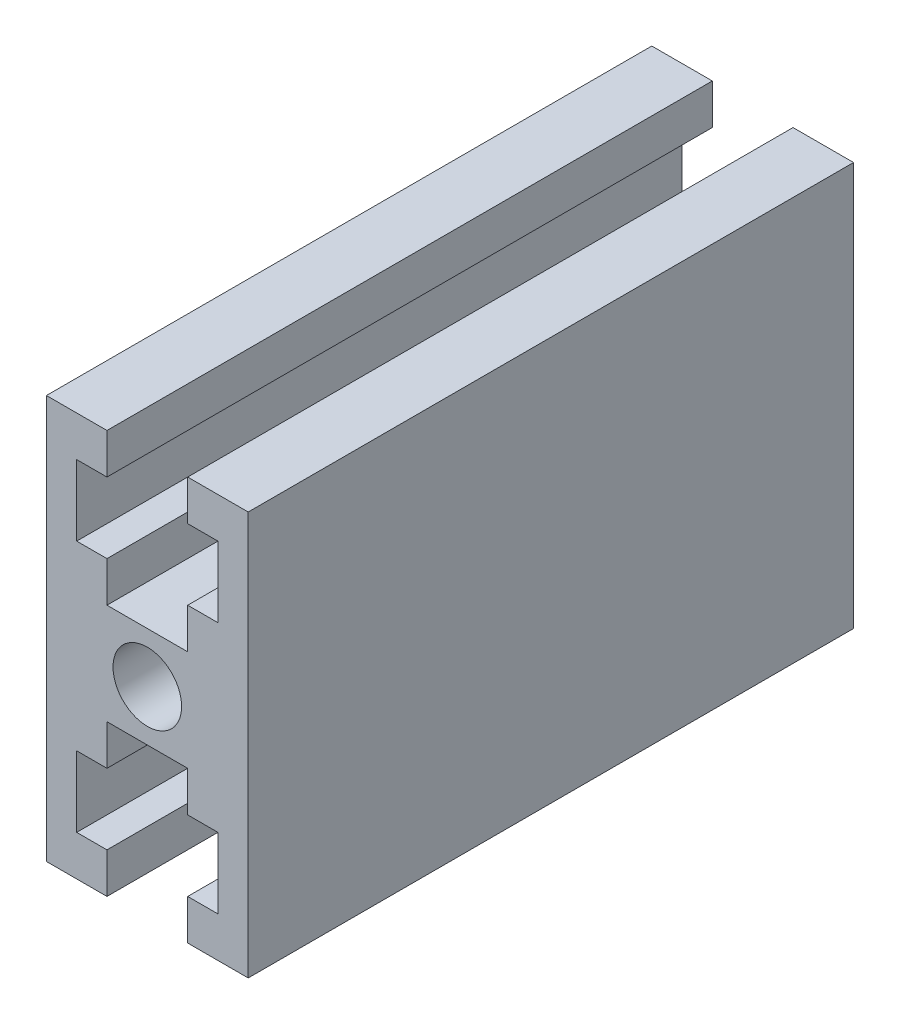
SolidWorks part; units mm, degrees
ref_plane "前视" through (0, 0, 0) normal (0, 0, 1) x (1, 0, 0)
ref_plane "上视" through (0, 0, 0) normal (0, 1, 0) x (1, 0, 0)
ref_plane "右视" through (0, 0, 0) normal (1, 0, 0) x (0, 0, -1)
sketch "草图2" plane through (0, 0, 0) normal (0, 0, 1) x (1, 0, 0)
  line L0 (0, 0) -> (6, 0)
  line L1 (6, 0) -> (6, -4)
  line L2 (6, -4) -> (3, -4)
  line L3 (3, -4) -> (3, -11)
  line L4 (3, -11) -> (6, -11)
  line L5 (6, -11) -> (6, -15)
  line L6 (6, -15) -> (14, -15)
  line L7 (14, -15) -> (14, -11)
  line L8 (14, -11) -> (17, -11)
  line L9 (17, -11) -> (17, -4)
  line L10 (17, -4) -> (14, -4)
  line L11 (14, -4) -> (14, 0)
  line L12 (14, 0) -> (20, 0)
  line L13 (20, 0) -> (20, -40)
  line L14 (0, 0) -> (0, -40)
  line L15 (-88.7936, -20) -> (42.7765, -20) construction
  line L16 (14, -40) -> (20, -40)
  line L17 (14, -36) -> (14, -40)
  line L18 (17, -36) -> (14, -36)
  line L19 (17, -29) -> (17, -36)
  line L20 (14, -29) -> (17, -29)
  line L21 (14, -25) -> (14, -29)
  line L22 (6, -25) -> (14, -25)
  line L23 (6, -29) -> (6, -25)
  line L24 (3, -29) -> (6, -29)
  line L25 (3, -36) -> (3, -29)
  line L26 (6, -36) -> (3, -36)
  line L27 (6, -40) -> (6, -36)
  line L28 (0, -40) -> (6, -40)
  circle A0 centre (10, -20) radius 3.4
  point P23 (0, -20)
  point P24 (20, -20)
  dimension "D1" = 4
  dimension "D11" = 6.8
  dimension "D2" = 7
  dimension "D3" = 14
  dimension "D4" = 8
  dimension "D5" = 6
  dimension "D6" = 6
  dimension "D7" = 3
  dimension "D8" = 4
  dimension "D9" = 20
  dimension "D10" = 10
extrude "凸台-拉伸1" add sketch "草图2" along normal blind 60
